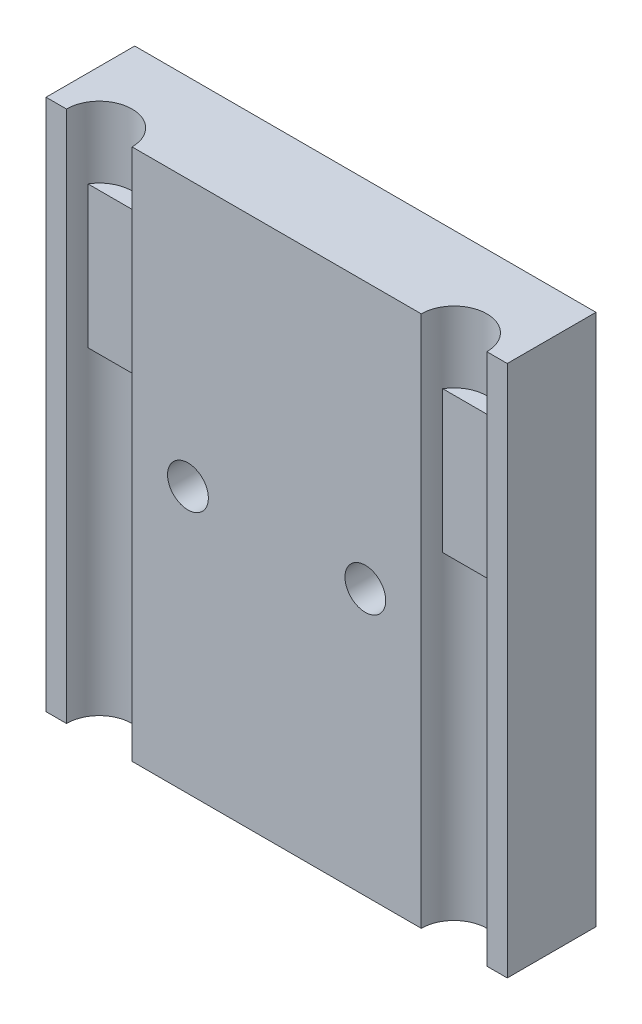
SolidWorks part; units mm, degrees
ref_plane "前视基准面" through (0, 0, 0) normal (0, 0, 1) x (1, 0, 0)
ref_plane "上视基准面" through (0, 0, 0) normal (0, 1, 0) x (1, 0, 0)
ref_plane "右视基准面" through (0, 0, 0) normal (1, 0, 0) x (0, 0, -1)
sketch "草图1" plane through (0, 0, 0) normal (0, 0, 1) x (1, 0, 0)
  line L1 (0, 0) -> (26, 0)
  line L2 (0, 0) -> (0, -30)
  line L3 (0, -30) -> (26, -30)
  line L4 (26, 0) -> (26, -30)
  dimension "D1" = 26
  dimension "D2" = 30
extrude "凸台-拉伸1" add sketch "草图1" along normal blind 5
sketch "草图2" plane through (0, 0, 0) normal (0, 1, 0) x (1, 0, 0)
  line L0 (26, -5) -> (0, -5) construction
  circle A0 centre (3, -5) radius 1.85
  circle A1 centre (23, -5) radius 1.85
  dimension "D2" = 3.7
  dimension "D3" = 3.7
  dimension "D1" = 20
  dimension "D4" = 3
extrude "切除-拉伸1" cut sketch "草图2" against normal blind 12
sketch "草图4" plane through (0, -12, 0) normal (0, 1, 0) x (1, 0, 0)
  line L2 (1.4125, -4.05) -> (4.5875, -4.05)
  line L3 (21.4125, -4.05) -> (24.5875, -4.05)
  arc A0 (24.85, -5) -> (21.15, -5) centre (23, -5) ccw construction
  arc A1 (4.85, -5) -> (1.15, -5) centre (3, -5) ccw construction
  arc A2 (24.5875, -4.05) -> (21.4125, -4.05) centre (23, -5) ccw
  arc A3 (4.5875, -4.05) -> (1.4125, -4.05) centre (3, -5) ccw
  dimension "D1" = 0.95
extrude "凸台-拉伸2" add sketch "草图4" along normal blind 8
sketch "草图5" plane through (0, -12, 0) normal (0, 1, 0) x (1, 0, 0)
  line L0 (4.85, -5) -> (1.15, -5) construction
  line L1 (24.85, -5) -> (21.15, -5) construction
  circle A0 centre (3, -5) radius 1.85
  circle A1 centre (23, -5) radius 1.85
  dimension "D1" = 3.7
  dimension "D2" = 3.7
extrude "切除-拉伸2" cut sketch "草图5" against normal through all
sketch "草图6" plane through (0, 0, 0) normal (0, 0, -1) x (-1, 0, 0)
  line L0 (-26, -30) -> (-26, 0) construction
  line L1 (0, 0) -> (0, -30) construction
  circle A0 centre (-18, -15) radius 1.15
  circle A1 centre (-8, -15) radius 1.15
  point P4 (0, 0)
  point P7 (-26, -15)
  point P8 (0, 0)
  point P11 (0, 0)
  point P12 (0, -15)
  point P15 (0, -14.4498)
  dimension "D1" = 2.3
  dimension "D2" = 2.3
  dimension "D3" = 8
  dimension "D4" = 10
extrude "切除-拉伸3" cut sketch "草图6" against normal blind 8
